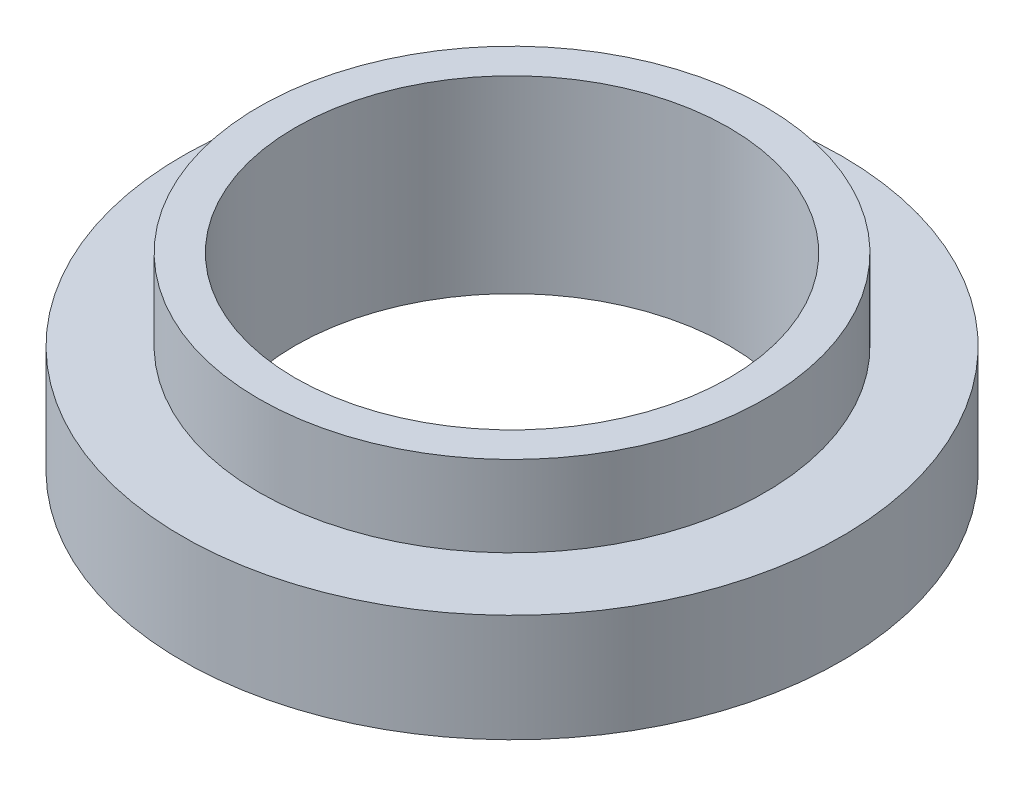
SolidWorks part; units mm, degrees
ref_plane "Front Plane" through (0, 0, 0) normal (0, 0, 1) x (1, 0, 0)
ref_plane "Top Plane" through (0, 0, 0) normal (0, 1, 0) x (1, 0, 0)
ref_plane "Right Plane" through (0, 0, 0) normal (1, 0, 0) x (0, 0, -1)
sketch "Sketch1" plane through (0, 0, 0) normal (0, 0, 1) x (1, 0, 0)
  line L0 (-31.85, 15.8333) -> (-31.85, 43.5438)
  line L1 (-54.35, 0) -> (-37.17, 0) construction
  line L2 (-31.85, 15.8333) -> (-31.85, 43.5438) construction
  line L3 (-31.85, 43.5438) -> (-37.17, 43.5438) construction
  line L4 (-37.17, 0) -> (-37.17, 43.5438) construction
  line L5 (-31.85, 43.5438) -> (-37.17, 43.5438)
  line L6 (-37.17, 43.5438) -> (-37.17, 31.6667)
  line L7 (-37.17, 31.6667) -> (-48.4, 31.6667)
  line L8 (-48.4, 31.6667) -> (-48.4, 15.8333)
  line L9 (-48.4, 15.8333) -> (-37.17, 15.8333) construction
  line L10 (-37.17, 15.8333) -> (-37.17, 0) construction
  line L11 (-37.17, 0) -> (-54.35, 0) construction
  line L12 (-40.7104, 15.8333) -> (-48.4, 15.8333)
  line L13 (0, 0) -> (0, 12.7515) construction
  line L14 (-40.7104, 15.8333) -> (-31.85, 15.8333)
  arc A0 (-37.17, 0) -> (-40.7104, 15.8333) centre (-40.7104, 7.5208) ccw construction
  dimension "D7" = 8.3125
  dimension "D1" = 31.85
  dimension "D2" = 5.32
  dimension "D3" = 43.5438
  dimension "D4" = 11.8771
  dimension "D5" = 48.4
  dimension "D6" = 15.8333
  dimension "D8" = 54.35
revolve "Revolve1" add sketch "Sketch1" angle 360 about L13
sketch "Sketch2" plane through (0, 31.6667, 0) normal (0, 1, 0) x (1, 0, 0)
  line L1 (5.9386, 79.1667) -> (-5.9386, 79.1667)
  line L2 (5.9386, 79.1667) -> (5.9386, 17.6333)
  line L3 (5.9386, 17.6333) -> (-5.9386, 17.6333)
  line L4 (-5.9386, 79.1667) -> (-5.9386, 17.6333)
  line L5 (5.9386, 79.1667) -> (-5.9386, 17.6333) construction
  line L6 (5.9386, 17.6333) -> (-5.9386, 79.1667) construction
  circle A0 centre (0, 0) radius 48.4 construction
  point P0 (0, 48.4)
  dimension "D1" = 11.8771
  dimension "D2" = 79.1667
sketch "Sketch7" plane through (0, 31.6667, 0) normal (0, 1, 0) x (1, 0, 0)
  point P3 (0, 0)
equation "\"D5@Sketch1\"=((\"Spring_inner_dia\"+\"Spring_wire_dia\")/2)*1.1"
equation "\"D6@Sketch1\"=\"Upper_Mount_largest_radius\"/1.68"
equation "\"D4@Sketch1\"=\"Upper_Mount_largest_radius\"/2.23960185"
equation "\"D2@Sketch1\"=\"Upper_Mount_largest_radius\"/5"
equation "\"D7@Sketch1\"=\"Upper_Mount_largest_radius\"/3.2"
equation "\"D1@Sketch1\"=\"Upper_Mount_largest_radius\"+\"Upper_mount_wall_thickness\"+1.25mm"
equation "\"D3@Sketch1\"=\"Upper_Mount_largest_radius\"/0.61087947"
equation "\"D2@Sketch2\"=\"Upper_Mount_largest_radius\"/0.336"
equation "\"D1@Sketch2\"=\"Upper_Mount_largest_radius\"/2.23960185"
equation "\"Upper_Mount_largest_radius\" =26.6"
equation "\"Upper_mount_wall_thickness\" =4"
equation "\"Lower_Mount_piston_rod_length\" =149"
equation "\"Lower_Mount_piston_rod_radius\"\t=3.4925"
equation "\"Piston_orifice_dia\"=0.30711"
equation "\"Spring_inner_dia\" =80"
equation "\"Spring_wire_dia\" =8"
